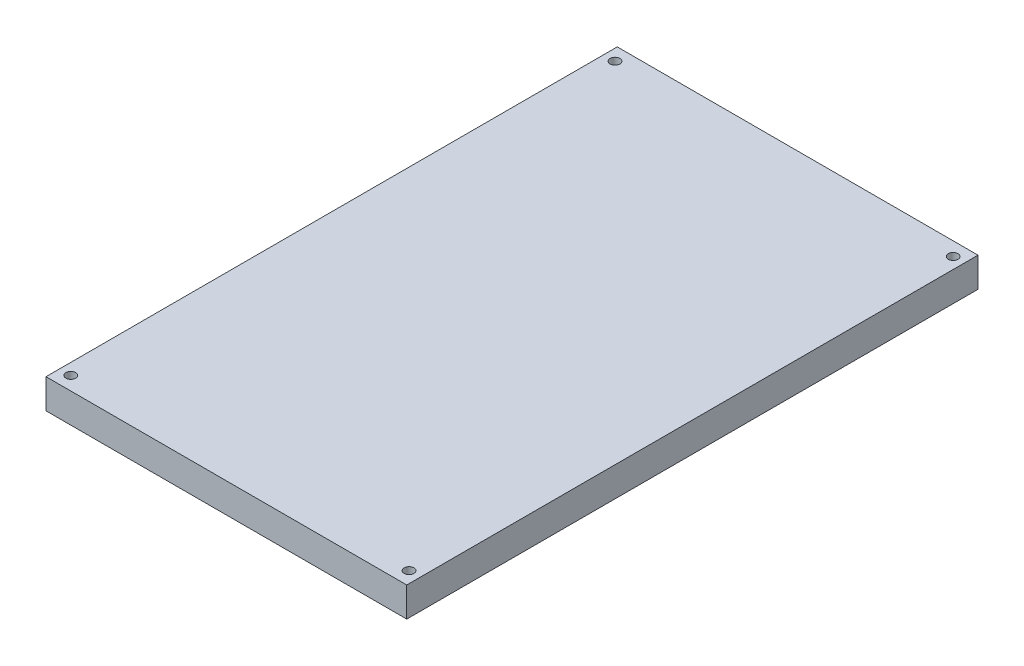
SolidWorks part; units mm, degrees
ref_plane "Front Plane" through (0, 0, 0) normal (0, 0, 1) x (1, 0, 0)
ref_plane "Top Plane" through (0, 0, 0) normal (0, 1, 0) x (1, 0, 0)
ref_plane "Right Plane" through (0, 0, 0) normal (1, 0, 0) x (0, 0, -1)
sketch "Sketch1" plane through (0, 0, 0) normal (0, 1, 0) x (1, 0, 0)
  line L1 (60.96, -96.5327) -> (-60.96, -96.5327)
  line L2 (60.96, -96.5327) -> (60.96, 96.5327)
  line L3 (60.96, 96.5327) -> (-60.96, 96.5327)
  line L4 (-60.96, -96.5327) -> (-60.96, 96.5327)
  line L5 (60.96, -96.5327) -> (-60.96, 96.5327) construction
  line L6 (60.96, 96.5327) -> (-60.96, -96.5327) construction
  circle A0 centre (-57.15, -91.9607) radius 1.651
  circle A1 centre (57.15, -91.948) radius 1.651
  circle A2 centre (57.15, 91.948) radius 1.651
  circle A3 centre (-57.15, 91.948) radius 1.651
  point P0 (0, 0)
  dimension "D5" = 3.302
  dimension "D1" = 193.0654
  dimension "D2" = 121.92
  dimension "D3" = 3.81
  dimension "D4" = 4.572
extrude "Boss-Extrude1" add sketch "Sketch1" along normal blind 10
